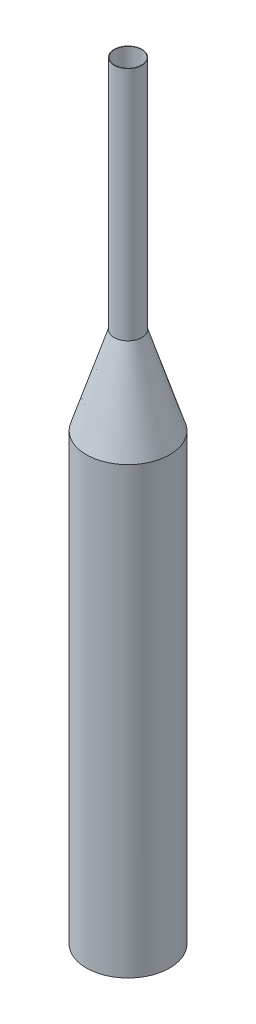
SolidWorks part; units mm, degrees
material "Ceramic Porcelain"
ref_plane "Front" through (0, 0, 0) normal (0, 0, 1) x (1, 0, 0)
ref_plane "Top" through (0, 0, 0) normal (0, 1, 0) x (1, 0, 0)
ref_plane "Right" through (0, 0, 0) normal (1, 0, 0) x (0, 0, -1)
ref_plane "Plane1" through (0, 5791.2, 0) normal (0, 1, 0) x (1, 0, 0)
sketch "Sketch1" plane through (0, 0, 0) normal (0, 1, 0) x (1, 0, 0)
  circle A0 centre (0, 0) radius 311.15
  circle A1 centre (0, 0) radius 314.325
  dimension "D1" = 622.3
  dimension "D2" = 628.65
extrude "Boss-Extrude1" add sketch "Sketch1" along normal blind 3352.8
sketch "Sketch2" plane through (0, 0, 0) normal (0, 0, 1) x (1, 0, 0)
  line L0 (0, 3352.8) -> (0, 5791.2) construction
  line L1 (314.325, 3352.8) -> (-314.325, 3352.8) construction
  line L2 (625.8511, 5791.2) -> (-625.8511, 5791.2) construction
  line L3 (-314.325, 3352.8) -> (-104.6261, 4013.2)
  line L4 (-104.6261, 4013.2) -> (-104.6261, 5791.2)
  line L5 (-104.6261, 5791.2) -> (-101.6, 5791.2)
  line L6 (-101.6, 5791.2) -> (-101.6, 4012.7311)
  line L7 (-101.6, 4012.7311) -> (-311.15, 3352.8)
  line L8 (-311.15, 3352.8) -> (-314.325, 3352.8)
  line L9 (-101.6, 4012.7311) -> (-104.6261, 4012.7311) construction
  line L11 (-104.6261, 4013.2) -> (-101.7419, 4012.2842) construction
  dimension "D1" = 203.2
  dimension "D2" = 1778
revolve "Revolve1" add sketch "Sketch2" angle 360 about L0
